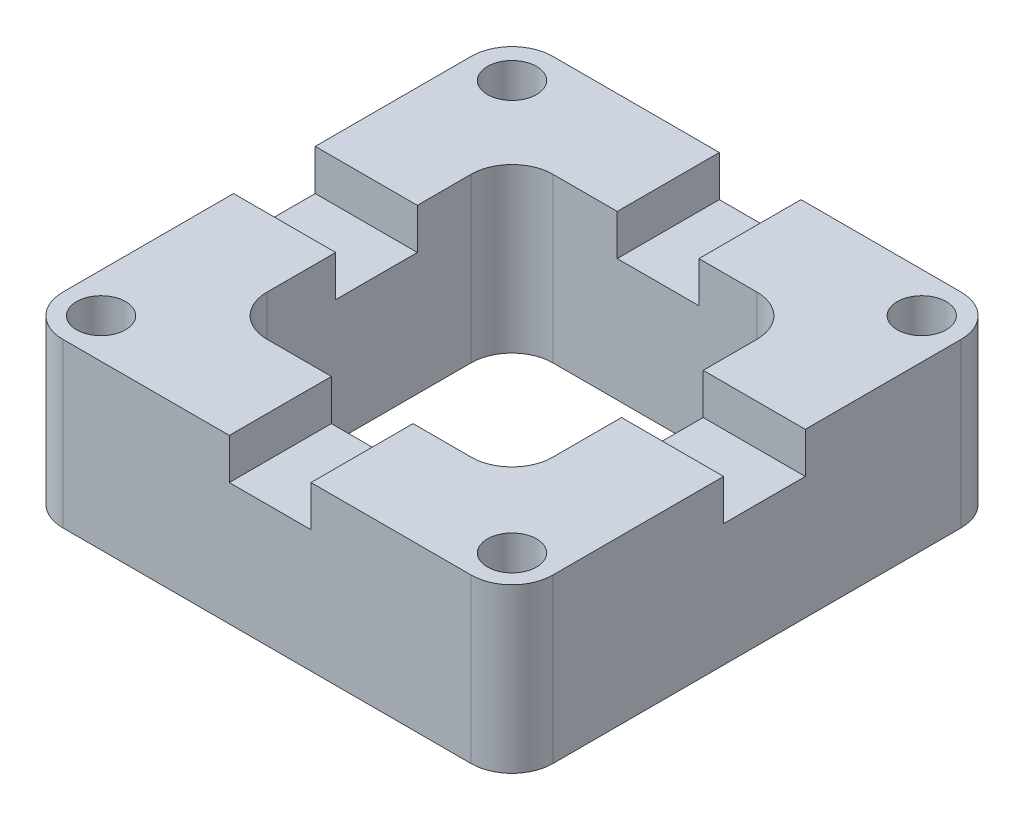
SolidWorks part; units mm, degrees
ref_plane "Front Plane" through (0, 0, 0) normal (0, 0, 1) x (1, 0, 0)
ref_plane "Top Plane" through (0, 0, 0) normal (0, 1, 0) x (1, 0, 0)
ref_plane "Right Plane" through (0, 0, 0) normal (1, 0, 0) x (0, 0, -1)
sketch "Sketch1" plane through (0, 0, 0) normal (0, 1, 0) x (1, 0, 0)
  line L0 (-9.6765, -35) -> (-9.6765, -60)
  line L1 (-50, 60) -> (50, 60)
  line L2 (-60, 50) -> (-60, -50)
  line L3 (-50, -60) -> (50, -60)
  line L4 (60, 50) -> (60, -50)
  line L5 (-60, 60) -> (60, -60) construction
  line L6 (-60, -60) -> (60, 60) construction
  line L7 (-25, 35) -> (25, 35)
  line L8 (-35, 25) -> (-35, -25)
  line L9 (-25, -35) -> (25, -35)
  line L10 (35, 25) -> (35, -25)
  line L11 (-35, 35) -> (35, -35) construction
  line L12 (-35, -35) -> (35, 35) construction
  line L13 (10.3235, -35) -> (10.3235, -60)
  line L14 (10.3235, 35) -> (10.3235, 60)
  line L15 (-9.6765, 35) -> (-9.6765, 60)
  line L16 (-35, 12.3216) -> (-60, 12.3216)
  line L17 (-35, -7.6784) -> (-60, -7.6784)
  line L18 (35, -7.6784) -> (60, -7.6784)
  line L19 (35, 12.3216) -> (60, 12.3216)
  arc A0 (-25, 35) -> (-35, 25) centre (-25, 25) ccw
  arc A1 (25, 35) -> (35, 25) centre (25, 25) cw
  arc A2 (25, -35) -> (35, -25) centre (25, -25) ccw
  arc A3 (-35, -25) -> (-25, -35) centre (-25, -25) ccw
  arc A4 (-60, -50) -> (-50, -60) centre (-50, -50) ccw
  arc A5 (50, -60) -> (60, -50) centre (50, -50) ccw
  arc A6 (50, 60) -> (60, 50) centre (50, 50) cw
  arc A7 (-50, 60) -> (-60, 50) centre (-50, 50) ccw
  circle A8 centre (50.1717, 50.1717) radius 6
  circle A9 centre (50.3161, -50.3161) radius 6
  circle A10 centre (-50.3161, -50.3161) radius 6
  circle A11 centre (-49.8828, 49.8828) radius 6
  point P0 (0, 0)
  point P6 (0, 0)
  dimension "D1" = 10
  dimension "D2" = 10
  dimension "D3" = 10
  dimension "D4" = 10
  dimension "D5" = 10
  dimension "D6" = 10
  dimension "D7" = 10
  dimension "D8" = 10
  dimension "D14" = 12
  dimension "D15" = 12
  dimension "D16" = 12
  dimension "D17" = 12
  dimension "D9" = 100
  dimension "D10" = 100
  dimension "D11" = 50
  dimension "D12" = 20
  dimension "D13" = 20
extrude "Boss-Extrude1" add sketch "Sketch1" along normal blind 30 contours L2 A4 L3 L0 L9 A3 L8 L17 A10 | L1 A7 L2 L16 L8 A0 L7 L15 A11 | A6 L1 L14 L7 A1 L10 L19 L4 A8 | L3 A5 L4 L18 L10 A2 L9 L13 A9 | L17 L8 L16 L2 | L19 L10 L18 L4 | L15 L7 L14 L1 | L13 L9 L0 L3
sketch "Sketch2" plane through (0, 30, 0) normal (0, 1, 0) x (1, 0, 0)
  line L0 (-9.2283, 60) -> (-9.2283, 35)
  line L1 (-50, 60) -> (50, 60) construction
  line L2 (-25, 35) -> (25, 35) construction
  line L3 (10.7717, 35) -> (10.7717, 60)
  line L4 (10.7717, 60) -> (-9.2283, 60)
  line L5 (-35, 11.8167) -> (-60, 11.8167)
  line L6 (-35, 25) -> (-35, -25) construction
  line L7 (-60, 50) -> (-60, -50) construction
  line L8 (-60, 11.8167) -> (-60, -8.1833)
  line L9 (-60, -8.1833) -> (-35, -8.1833)
  line L10 (-35, -8.1833) -> (-35, 11.8167)
  line L11 (-9.2283, -35) -> (-9.2283, -60)
  line L12 (-25, -35) -> (25, -35) construction
  line L13 (-50, -60) -> (50, -60) construction
  line L14 (10.7717, -60) -> (10.7717, -35)
  line L15 (10.7717, -35) -> (-9.2283, -35)
  line L16 (35, 11.8167) -> (60, 11.8167)
  line L17 (35, 25) -> (35, -25) construction
  line L18 (60, 50) -> (60, -50) construction
  line L19 (60, 11.8167) -> (60, -8.1833)
  line L20 (60, -8.1833) -> (35, -8.1833)
  line L21 (35, -8.1833) -> (35, 11.8167)
  line M8 (60, -50) -> (60, 50)
  arc M9 (60, 50) -> (50, 60) centre (50, 50) ccw
  line M10 (50, 60) -> (-50, 60)
  arc M11 (-50, 60) -> (-60, 50) centre (-50, 50) ccw
  line M12 (-60, 50) -> (-60, -50)
  arc M13 (-60, -50) -> (-50, -60) centre (-50, -50) ccw
  line M14 (-50, -60) -> (50, -60)
  arc M15 (50, -60) -> (60, -50) centre (50, -50) ccw
  circle M16 centre (-50.3161, -50.3161) radius 6
  arc M17 (25, 35) -> (35, 25) centre (25, 25) cw
  line M18 (35, 25) -> (35, -25)
  arc M19 (35, -25) -> (25, -35) centre (25, -25) cw
  line M20 (25, -35) -> (-25, -35)
  arc M21 (-25, -35) -> (-35, -25) centre (-25, -25) cw
  line M22 (-35, -25) -> (-35, 25)
  arc M23 (-35, 25) -> (-25, 35) centre (-25, 25) cw
  line M24 (-25, 35) -> (25, 35)
  circle M25 centre (-49.8828, 49.8828) radius 6
  circle M26 centre (50.3161, -50.3161) radius 6
  circle M27 centre (50.1717, 50.1717) radius 6
  dimension "D1" = 25
  dimension "D2" = 20
  dimension "D3" = 20
  dimension "D4" = 25
  dimension "D5" = 20
extrude "Boss-Extrude2" add sketch "Sketch2" along normal blind 10 contours L5 L0 M22 M23 M24 M10 M11 M12 M25 | L16 L3 M18 M8 M9 M10 M24 M17 M27 | L20 L14 M8 M18 M19 M20 M14 M15 M26 | L11 L9 M20 M21 M22 M12 M13 M14 M16
